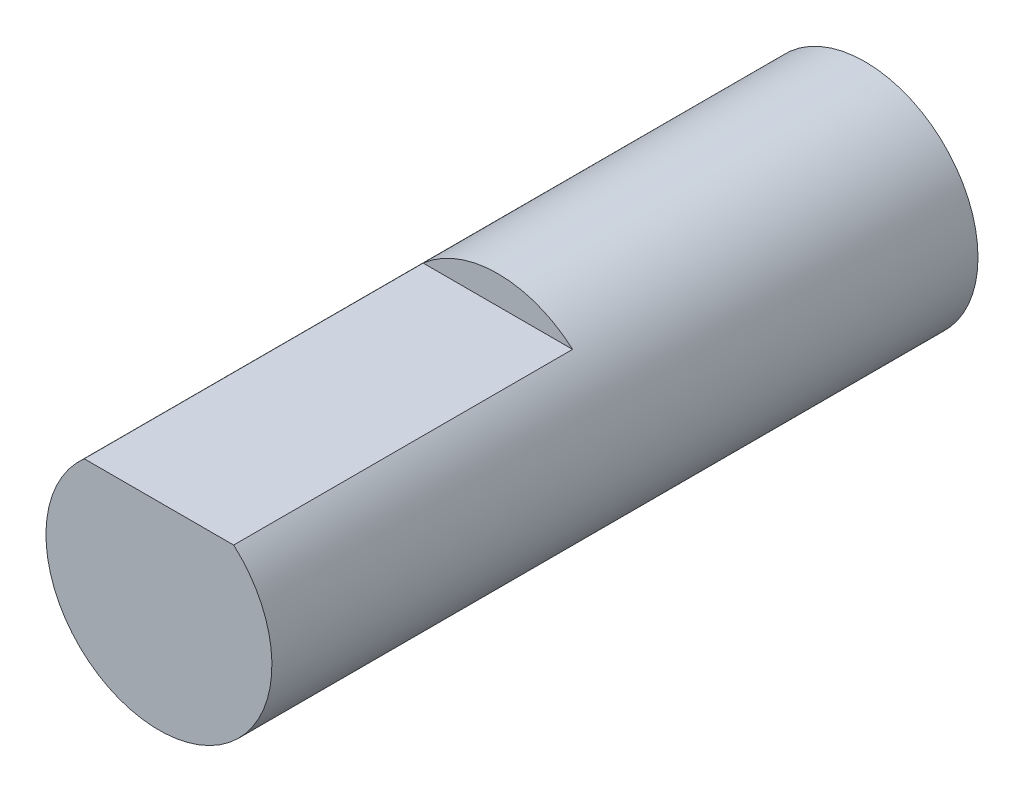
SolidWorks part; units mm, degrees
material "201 Annealed Stainless Steel (SS)"
ref_plane "Front Plane" through (0, 0, 0) normal (0, 0, 1) x (1, 0, 0)
ref_plane "Top Plane" through (0, 0, 0) normal (0, 1, 0) x (1, 0, 0)
ref_plane "Right Plane" through (0, 0, 0) normal (1, 0, 0) x (0, 0, -1)
sketch "Sketch1" plane through (0, 0, 0) normal (0, 0, 1) x (1, 0, 0)
  circle A0 centre (0, 0) radius 4
  dimension "D1" = 8
extrude "Boss-Extrude1" add sketch "Sketch1" along normal blind 25
sketch "Sketch2" plane through (0, 0, 25) normal (0, 0, 1) x (1, 0, 0)
  line L0 (0, 4) -> (0, 0) construction
  line L1 (-2.6458, 3) -> (2.6458, 3)
  circle A0 centre (0, 0) radius 4 construction
  arc A1 (-2.6458, 3) -> (2.6458, 3) centre (0, 0) cw
  point P8 (0, 3)
  point P9 (0, 3)
  dimension "D1" = 1
extrude "Cut-Extrude1" cut sketch "Sketch2" against normal blind 12
